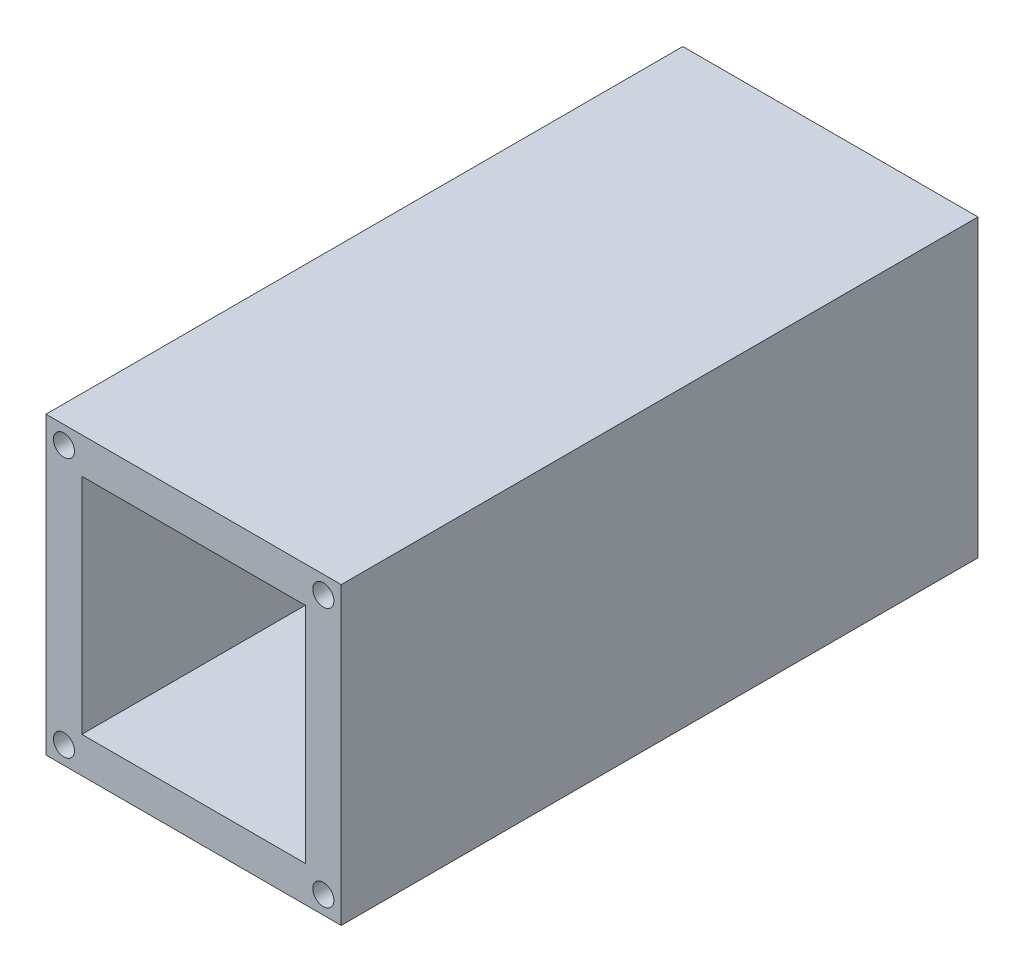
SolidWorks part; units mm, degrees
ref_plane "Alzado" through (0, 0, 0) normal (0, 0, 1) x (1, 0, 0)
ref_plane "Planta" through (0, 0, 0) normal (0, 1, 0) x (1, 0, 0)
ref_plane "Vista lateral" through (0, 0, 0) normal (1, 0, 0) x (0, 0, -1)
sketch "Croquis1" plane through (0, 0, 0) normal (0, 0, 1) x (1, 0, 0)
  line L1 (17.5, -17.5) -> (-17.5, -17.5)
  line L2 (17.5, -17.5) -> (17.5, 17.5)
  line L3 (17.5, 17.5) -> (-17.5, 17.5)
  line L4 (-17.5, -17.5) -> (-17.5, 17.5)
  line L5 (17.5, -17.5) -> (-17.5, 17.5) construction
  line L6 (17.5, 17.5) -> (-17.5, -17.5) construction
  line L11 (10.75, -10.75) -> (-15.75, 15.75) construction
  point P0 (0, 0)
  point P5 (0, 0)
  dimension "D1" = 35
extrude "Saliente-Extruir2" add sketch "Croquis1" along normal blind 75.5
sketch "Croquis2" plane through (0, 0, 75.5) normal (0, 0, 1) x (1, 0, 0)
  line L1 (13.25, -13.25) -> (-13.25, -13.25)
  line L2 (13.25, -13.25) -> (13.25, 13.25)
  line L3 (13.25, 13.25) -> (-13.25, 13.25)
  line L4 (-13.25, -13.25) -> (-13.25, 13.25)
  line L5 (13.25, -13.25) -> (-13.25, 13.25) construction
  line L6 (13.25, 13.25) -> (-13.25, -13.25) construction
  point P0 (0, 0)
  dimension "D1" = 26.5
extrude "Cortar-Extruir1" cut sketch "Croquis2" against normal blind 80
sketch "Croquis4" plane through (0, 0, 75.5) normal (0, 0, 1) x (1, 0, 0)
  circle A0 centre (-15.375, 15.38) radius 1.25
  circle A1 centre (15.38, 15.38) radius 1.25
  circle A2 centre (15.38, -15.38) radius 1.25
  circle A3 centre (-15.375, -15.38) radius 1.25
  dimension "D3" = 2.5
  dimension "D5" = 2.5
  dimension "D7" = 2.5
  dimension "D8" = 2.5
extrude "Cortar-Extruir2" cut sketch "Croquis4" against normal blind 10
sketch "Croquis9" plane through (0, 0, 0) normal (0, 0, -1) x (-1, 0, 0)
  circle A0 centre (-15.38, 15.38) radius 1.25
  circle A1 centre (15.38, 15.38) radius 1.25
  circle A2 centre (15.38, -15.38) radius 1.25
  circle A3 centre (-15.38, -15.38) radius 1.25
  dimension "D3" = 2.5
  dimension "D5" = 2.5
  dimension "D7" = 2.5
  dimension "D8" = 2.5
extrude "Cortar-Extruir5" cut sketch "Croquis9" against normal blind 10
sketch "Croquis11" plane through (0, 0, 0) normal (0, 0, -1) x (-1, 0, 0)
  line L1 (-13.25, -13.25) -> (13.25, -13.25)
  line L2 (-13.25, -13.25) -> (-13.25, 13.25)
  line L3 (-13.25, 13.25) -> (13.25, 13.25)
  line L4 (13.25, -13.25) -> (13.25, 13.25)
extrude "Saliente-Extruir3" add sketch "Croquis11" against normal blind 37
sketch "Croquis13" plane through (0, 0, 0) normal (0, 0, -1) x (-1, 0, 0)
  line L1 (13.25, -13.25) -> (-13.25, -13.25)
  line L2 (13.25, -13.25) -> (13.25, 13.25)
  line L3 (13.25, 13.25) -> (-13.25, 13.25)
  line L4 (-13.25, -13.25) -> (-13.25, 13.25)
  line L5 (13.25, -13.25) -> (-13.25, 13.25) construction
  line L6 (13.25, 13.25) -> (-13.25, -13.25) construction
  point P0 (0, 0)
  dimension "D1" = 26.5
extrude "Cortar-Extruir6" cut sketch "Croquis13" against normal blind 30
sketch "Croquis14" plane through (0, 0, 37) normal (0, 0, 1) x (1, 0, 0)
  line L0 (13.3, 0) -> (-13.3, 0)
  line L1 (-13.35, -4.9997) -> (-13.25, 4.9997)
  line L2 (-13.25, 13.25) -> (-13.25, -13.25) construction
  line L3 (13.35, -4.9997) -> (13.25, 4.9997)
  line L4 (13.25, -13.25) -> (13.25, 13.25) construction
  line L5 (13.25, 4.9997) -> (8.3147, 8.6525)
  line L6 (13.35, -4.9997) -> (8.3147, -8.6525)
  line L7 (-13.35, -4.9997) -> (-8.3147, -8.6525)
  line L8 (-13.25, 4.9997) -> (-8.3147, 8.6525)
  arc A1 (-8.3147, 8.6525) -> (8.3147, 8.6525) centre (0, -2.5817) cw
  arc A2 (8.3147, -8.6525) -> (-8.3147, -8.6525) centre (0, 2.8093) cw
  point P4 (0, 0)
  point P10 (-13.3, 0)
  point P15 (13.3, 0)
  line M2 (13.25, -13.25) -> (13.25, 13.25)
  line M4 (-13.25, 13.25) -> (-13.25, -13.25)
  dimension "D1" = 5
  dimension "D2" = 5
  dimension "D4" = 6.14
extrude "Cortar-Extruir7" cut sketch "Croquis14" against normal up to next contours A2 L6 L0 L7 M2 M4 | A1 L8 L0 L5 M4 M2
